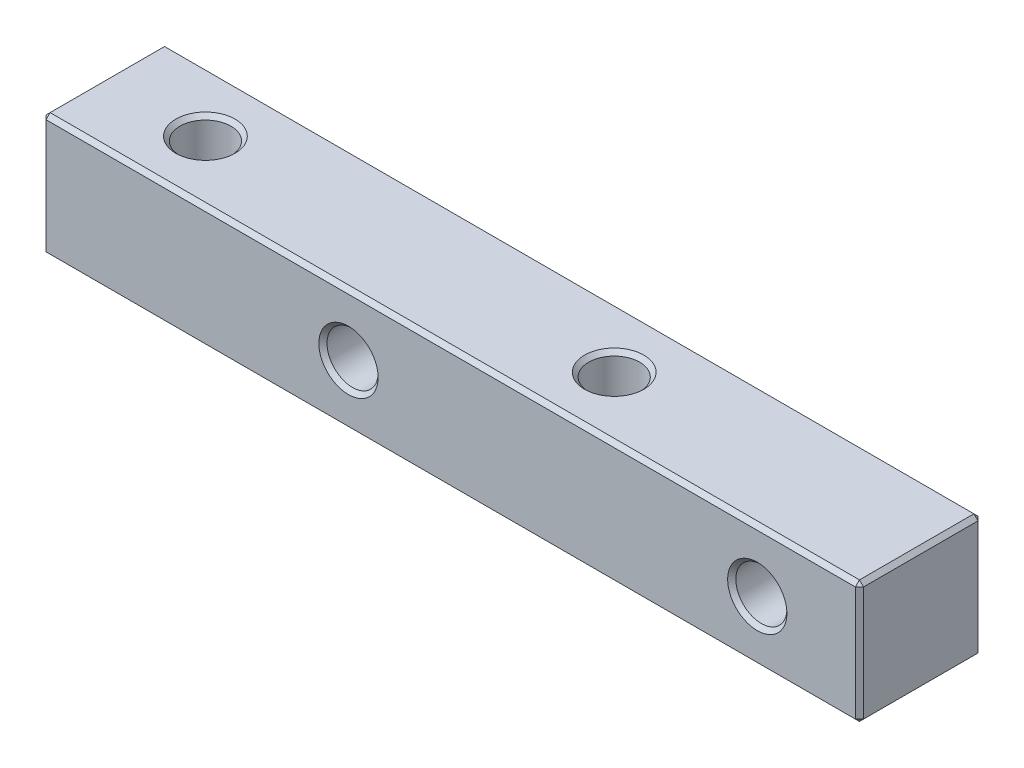
SolidWorks part; units mm, degrees
ref_plane "前视基准面" through (0, 0, 0) normal (0, 0, 1) x (1, 0, 0)
ref_plane "上视基准面" through (0, 0, 0) normal (0, 1, 0) x (1, 0, 0)
ref_plane "右视基准面" through (0, 0, 0) normal (1, 0, 0) x (0, 0, -1)
sketch "草图1" plane through (0, 0, 0) normal (0, 1, 0) x (1, 0, 0)
  line L1 (-20, 3) -> (20, 3)
  line L2 (-20, 3) -> (-20, -3)
  line L3 (-20, -3) -> (20, -3)
  line L4 (20, 3) -> (20, -3)
  line L5 (-20, 3) -> (20, -3) construction
  line L6 (-20, -3) -> (20, 3) construction
  point P0 (0, 0)
  dimension "D1" = 6
  dimension "D2" = 40
extrude "凸台-拉伸1" add sketch "草图1" along normal mid plane 6
hole_wizard "M3 螺纹孔1" positions "草图4" profile "草图6" tap size "M3" standard "GB" end condition through all
sketch "草图4" plane through (0, 3, 0) normal (0, 1, 0) x (1, 0, 0)
  line L0 (-20, 3) -> (-20, -3) construction
  line L1 (0, 0) -> (-50000, 0) construction
  point P0 (-15, 0)
  point P2 (5, 0)
  dimension "D1" = 5
  dimension "D2" = 20
sketch "草图6" plane through (-15, 3, 0) normal (1, 0, 0) x (0, 0, 1)
  line L0 (0, 0) -> (0, 6)
  line L1 (0, 6) -> (1.25, 6)
  line L2 (1.25, 6) -> (1.25, 0)
  line L5 (1.25, 0) -> (0, 0)
  line L11 (0, -6.35) -> (0, 107.95) construction
  dimension "通孔螺纹孔钻头直径" = 2.5
  dimension "通孔螺纹孔钻头深度" = 6
cosmetic thread "孔螺蚊线1" parameters "D2"=3
cosmetic thread "孔螺蚊线2" parameters "D2"=3
hole_wizard "M3 螺纹孔2" positions "草图7" profile "草图8" tap size "M3" standard "GB" end condition through all
sketch "草图7" plane through (0, 0, -3) normal (0, 0, -1) x (-1, 0, 0)
  line L0 (0, 0) -> (-50000, 0) construction
  line L1 (-20, 3) -> (-20, -3) construction
  point P0 (-15, 0)
  point P2 (5, 0)
  dimension "D1" = 5
  dimension "D2" = 20
sketch "草图8" plane through (15, 0, -3) normal (1, 0, 0) x (0, 1, 0)
  line L0 (0, 0) -> (0, 6)
  line L1 (0, 6) -> (1.25, 6)
  line L2 (1.25, 6) -> (1.25, 0)
  line L5 (1.25, 0) -> (0, 0)
  line L11 (0, -6.35) -> (0, 107.95) construction
  dimension "通孔螺纹孔钻头直径" = 2.5
  dimension "通孔螺纹孔钻头深度" = 6
cosmetic thread "孔螺蚊线3" parameters "D2"=3
cosmetic thread "孔螺蚊线4" parameters "D2"=3
chamfer "倒角1" distance 0.2 angle 45 20 edges at (5, -3, 1.25) (-15, -3, 1.25) (-6.25, 0, 3) (13.75, 0, 3) (5, 3, 1.25) (-15, 3, 1.25) (-20, -3, 0) (20, -3, 0) (-20, 0, 3) (0, -3, 3) (20, 0, 3) (0, 3, 3) (-20, 3, 0) (20, 3, 0) (20, 0, -3) (0, 3, -3) (-20, 0, -3) (0, -3, -3) (-6.25, 0, -3) (13.75, 0, -3)
